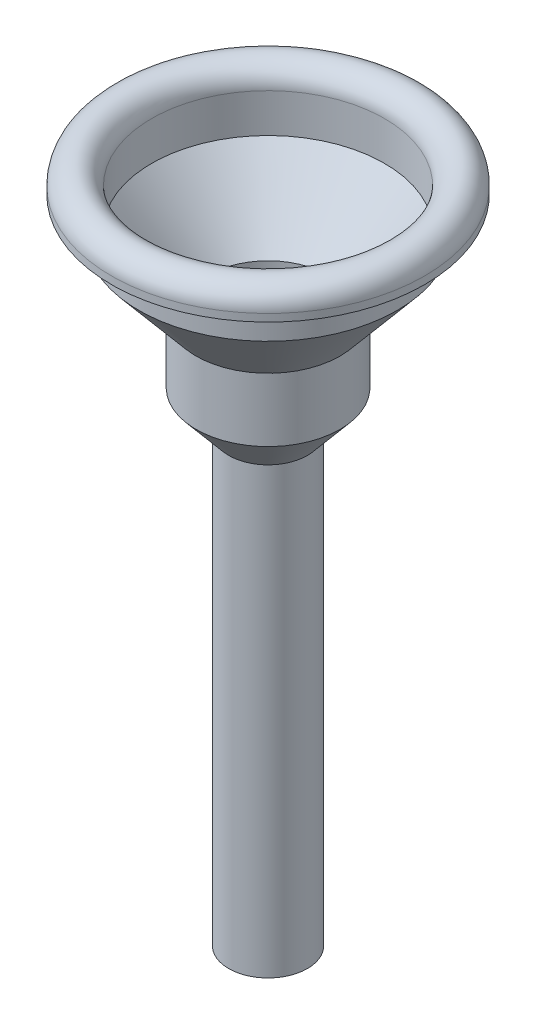
SolidWorks part; units mm, degrees
ref_plane "前视基准面" through (0, 0, 0) normal (0, 0, 1) x (1, 0, 0)
ref_plane "上视基准面" through (0, 0, 0) normal (0, 1, 0) x (1, 0, 0)
ref_plane "右视基准面" through (0, 0, 0) normal (1, 0, 0) x (0, 0, -1)
sketch "草图1" plane through (0, 0, 0) normal (0, 0, 1) x (1, 0, 0)
  line L0 (0, -31.3486) -> (0, 31.3486) construction
  line L1 (0, 0) -> (0.27, 0) construction
  line L2 (0.27, 0) -> (0.31, 0)
  line L3 (0.31, 0) -> (0.31, 3.5)
  line L4 (0.31, 3.5) -> (0.5671, 3.8064)
  line L5 (0.5671, 3.8064) -> (0.5671, 4.3064)
  line L6 (0.5671, 4.3064) -> (1.0171, 4.8426)
  line L7 (1.0171, 4.8426) -> (1.0171, 5.185)
  line L8 (0.21, 0.08) -> (0.21, 0.08)
  line L9 (1.1324, 5.185) -> (1.1324, 5.126)
  line L11 (0.27, 3.6079) -> (0.4671, 3.8428)
  line L12 (0.4671, 3.8428) -> (0.4671, 4.3428)
  line L13 (0.4671, 4.3428) -> (0.9171, 4.879)
  line L14 (0.9171, 4.879) -> (0.9171, 5.185)
  line L15 (1.2324, 5.185) -> (1.2324, 5.126)
  line L16 (1.1324, 5.126) -> (1.2324, 5.126)
  line L17 (0.27, 0) -> (0.27, 3.6079)
  line L19 (0.21, 3.5364) -> (0.4671, 3.8428) construction
  line L20 (0.21, 0.08) -> (0.21, 3.5364) construction
  arc A0 (1.0171, 5.185) -> (1.1324, 5.185) centre (1.0747, 5.185) cw
  arc A1 (0.9171, 5.185) -> (1.2324, 5.185) centre (1.0747, 5.185) cw
  point P4 (0, 0)
  point P41 (1.0747, 5.3426)
  dimension "D1" = 0.27
  dimension "D2" = 0.31
  dimension "D3" = 3.5
  dimension "D4" = 40
  dimension "D5" = 0.1
  dimension "D6" = 0.4
  dimension "D7" = 0.5
  dimension "D8" = 0.7
  dimension "D9" = 0.5
revolve "旋转1" add sketch "草图1" angle 360 about L0
